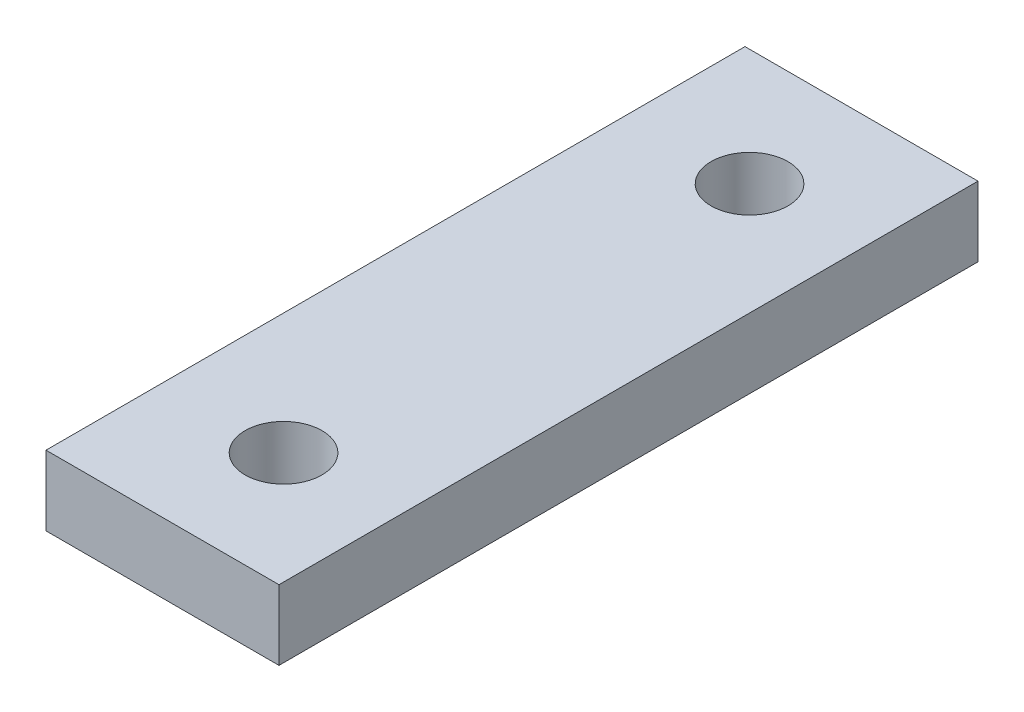
SolidWorks part; units mm, degrees
ref_plane "Front Plane" through (0, 0, 0) normal (0, 0, 1) x (1, 0, 0)
ref_plane "Top Plane" through (0, 0, 0) normal (0, 1, 0) x (1, 0, 0)
ref_plane "Right Plane" through (0, 0, 0) normal (1, 0, 0) x (0, 0, -1)
sketch "Sketch1" plane through (0, 0, 0) normal (0, 1, 0) x (1, 0, 0)
  line L0 (-1000, 15) -> (49000, 15) construction
  line L1 (0, 0) -> (10, 0)
  line L2 (0, 0) -> (0, 30)
  line L3 (0, 30) -> (10, 30)
  line L4 (10, 0) -> (10, 30)
  circle A0 centre (5.1945, 25) radius 1.65
  circle A1 centre (5.1945, 5) radius 1.65
  point P10 (0, 15)
  dimension "D4" = 3.3
  dimension "D1" = 10
  dimension "D2" = 30
  dimension "D3" = 5
extrude "Boss-Extrude1" add sketch "Sketch1" along normal blind 3
